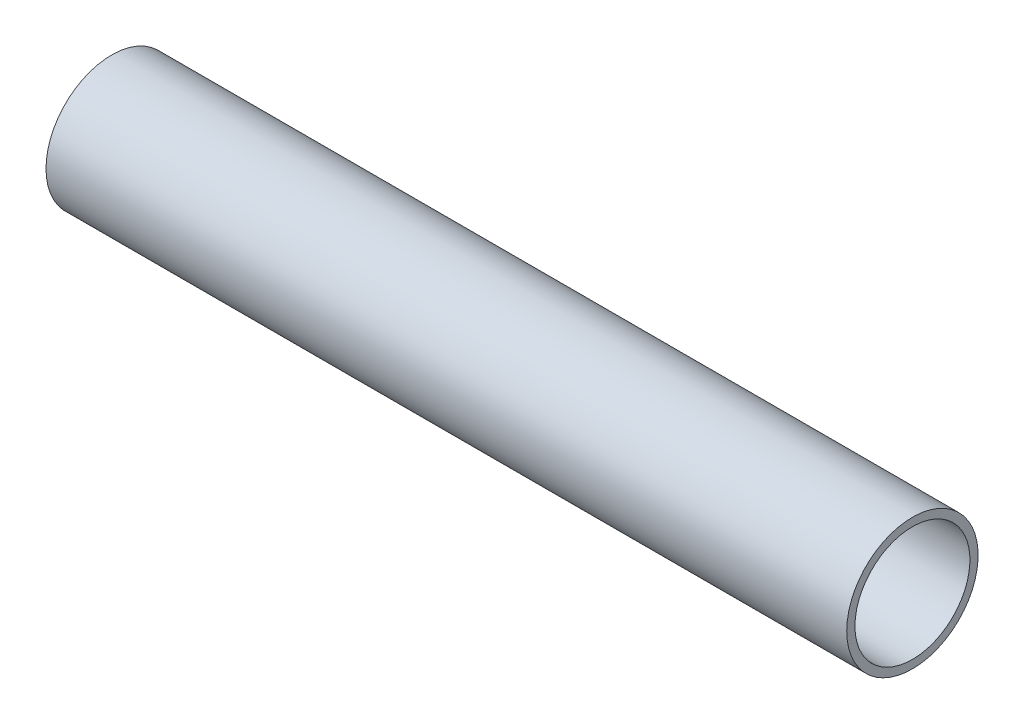
SolidWorks part; units mm, degrees
ref_plane "Plan de face" through (0, 0, 0) normal (0, 0, 1) x (1, 0, 0)
ref_plane "Plan de dessus" through (0, 0, 0) normal (0, 1, 0) x (1, 0, 0)
ref_plane "Plan de droite" through (0, 0, 0) normal (1, 0, 0) x (0, 0, -1)
sketch "Esquisse1" plane through (0, 0, 0) normal (0, 0, 1) x (1, 0, 0)
  line L0 (-82.95, 0) -> (123.55, 0) construction
  line L1 (-74.9, 16) -> (-74.9, 14)
  line L2 (-74.9, 14) -> (120.1, 14)
  line L3 (120.1, 14) -> (120.1, 16)
  line L4 (120.1, 16) -> (-74.9, 16)
  dimension "D1" = 2
  dimension "D2" = 16
  dimension "D3" = 195
revolve "Révolution1" add sketch "Esquisse1" angle 360 about L0
